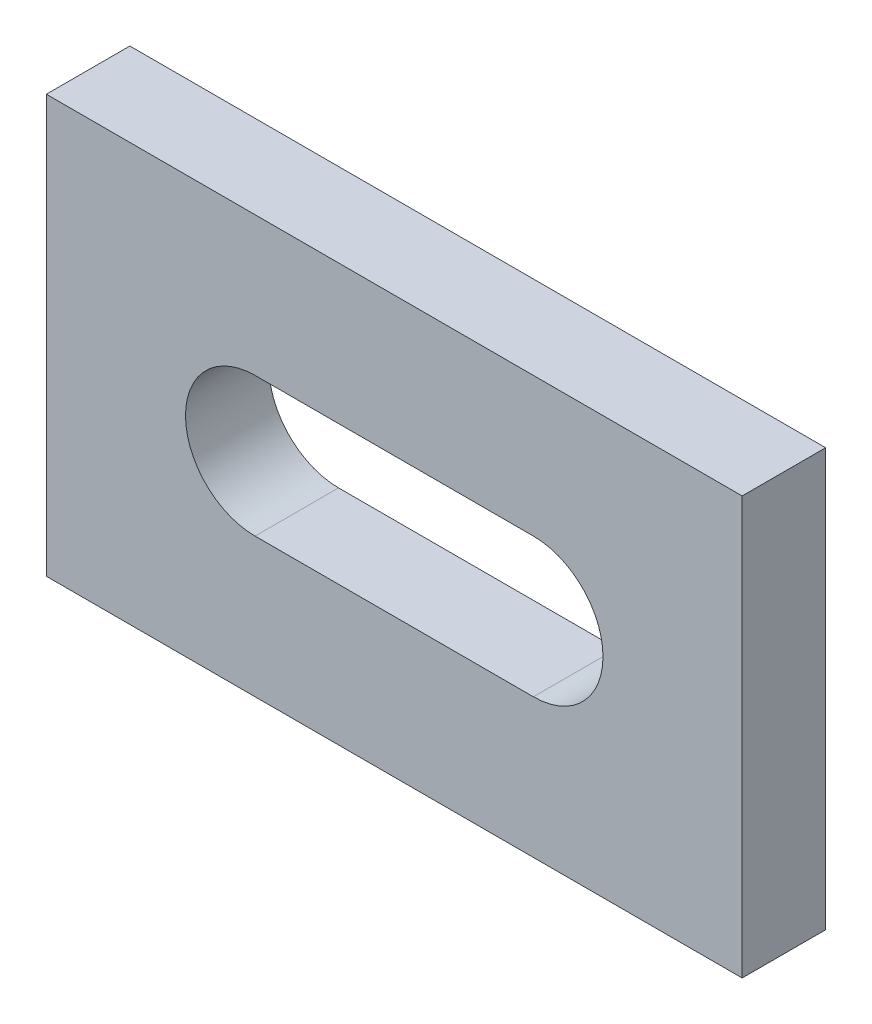
SolidWorks part; units mm, degrees
ref_plane "Front" through (0, 0, 0) normal (0, 0, 1) x (1, 0, 0)
ref_plane "Top" through (0, 0, 0) normal (0, 1, 0) x (1, 0, 0)
ref_plane "Right" through (0, 0, 0) normal (1, 0, 0) x (0, 0, -1)
sketch "Sketch1" plane through (0, 0, 0) normal (0, 0, 1) x (1, 0, 0)
  line L0 (30, 30) -> (45, 30) construction
  line L1 (0, 0) -> (150, 0)
  line L2 (0, 0) -> (0, 90)
  line L3 (0, 90) -> (150, 90)
  line L4 (150, 0) -> (150, 90)
  line L5 (45, 30) -> (105, 30)
  line L6 (45, 60) -> (105, 60)
  line L7 (30, 30) -> (30, 45) construction
  line L8 (45, 45) -> (45, 53.3716) construction
  line L21 (105, 45) -> (105, 53.3716) construction
  arc A0 (45, 60) -> (45, 30) centre (45, 45) ccw
  arc A1 (105, 30) -> (105, 60) centre (105, 45) ccw
  point P13 (120, 45)
  point P28 (45, 53.3716)
  point P29 (45, 45)
  dimension "D3" = 30
  dimension "D1" = 150
  dimension "D2" = 90
  dimension "D4" = 90
  dimension "D7" = 30
  dimension "D8" = 30
extrude "Boss-Extrude1" add sketch "Sketch1" along normal blind 18
